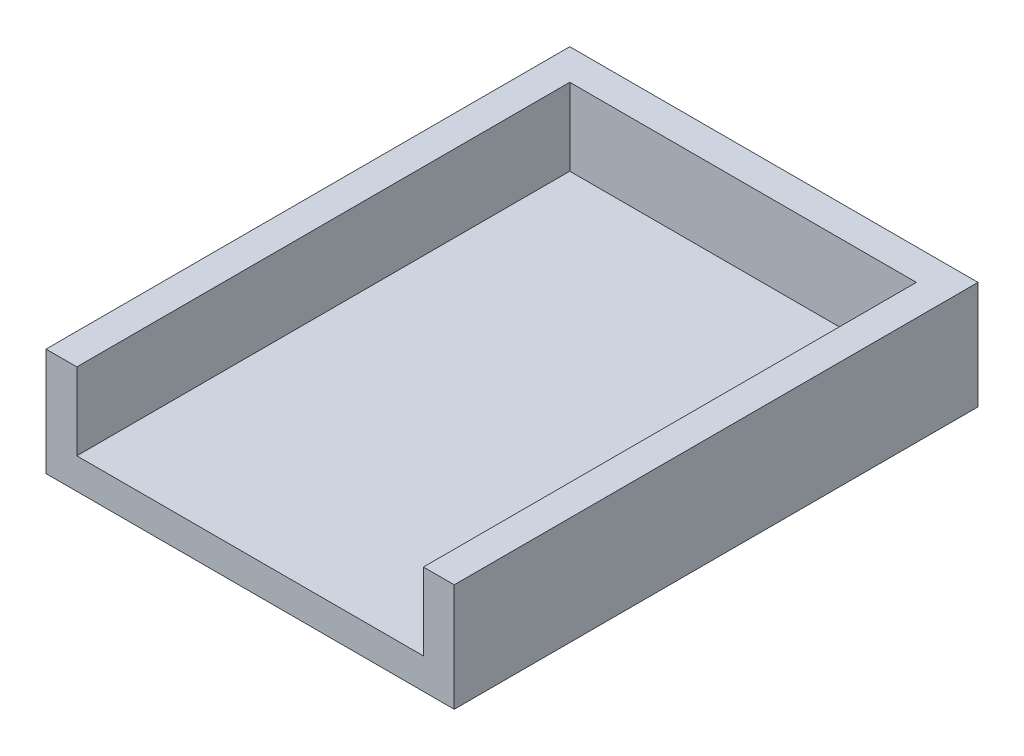
SolidWorks part; units mm, degrees
ref_plane "Front Plane" through (0, 0, 0) normal (0, 0, 1) x (1, 0, 0)
ref_plane "Top Plane" through (0, 0, 0) normal (0, 1, 0) x (1, 0, 0)
ref_plane "Right Plane" through (0, 0, 0) normal (1, 0, 0) x (0, 0, -1)
sketch "Sketch1" plane through (0, 0, 0) normal (0, 1, 0) x (1, 0, 0)
  line L1 (-11.25, 16) -> (11.25, 16)
  line L2 (-11.25, 16) -> (-11.25, -16)
  line L3 (-11.25, -16) -> (11.25, -16)
  line L4 (11.25, 16) -> (11.25, -16)
  line L5 (-11.25, 16) -> (11.25, -16) construction
  line L6 (-11.25, -16) -> (11.25, 16) construction
  point P0 (0, 0)
  dimension "D1" = 32
  dimension "D2" = 22.5
extrude "Boss-Extrude1" add sketch "Sketch1" along normal blind 2
sketch "Sketch3" plane through (0, 2, 0) normal (0, 1, 0) x (1, 0, 0)
  line L1 (-11.25, 16) -> (11.25, 16)
  line L2 (-11.25, 16) -> (-11.25, -16)
  line L3 (-11.25, -16) -> (11.25, -16)
  line L4 (11.25, 16) -> (11.25, -16)
  line L7 (-13.25, 18) -> (13.25, 18)
  line L8 (-11.25, -16) -> (-13.25, -16)
  line L9 (11.25, -16) -> (13.25, -16)
  line L10 (13.25, 18) -> (13.25, -16)
  line L11 (-13.25, -16) -> (-13.25, 18)
  line L20 (-13.25, -18) -> (13.25, -18) construction
  line L21 (13.25, 18) -> (13.25, -18) construction
  line L22 (-13.25, 18) -> (-13.25, -18) construction
  line M9 (11.25, -16) -> (11.25, 16)
  line M10 (11.25, 16) -> (-11.25, 16)
  line M11 (-11.25, 16) -> (-11.25, -16)
  dimension "D1" = 2
extrude "Boss-Extrude3" add sketch "Sketch3" along normal blind 7 from surface at -2 contours L11 L8 L9 L10 L7 M11 M10 M9 | L2 L1 L4 L3
